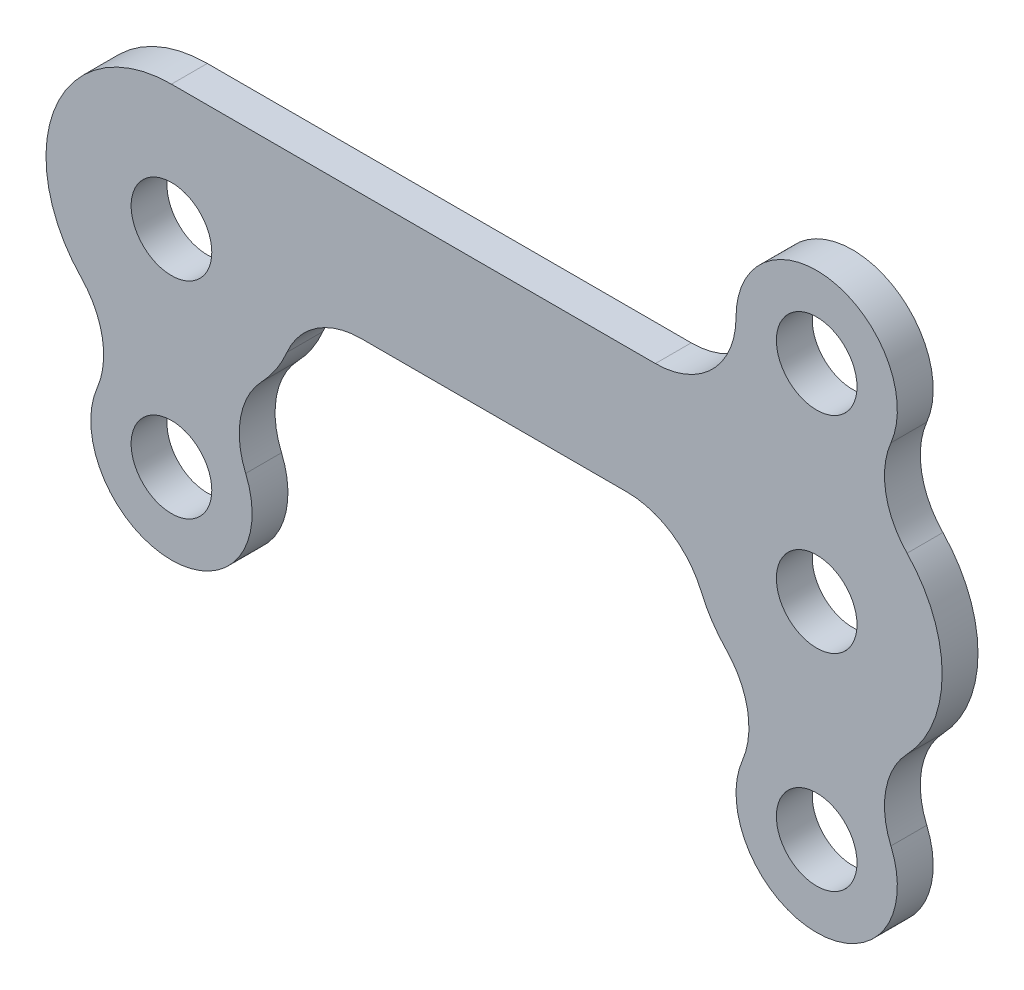
SolidWorks part; units mm, degrees
ref_plane "Front Plane" through (0, 0, 0) normal (0, 0, 1) x (1, 0, 0)
ref_plane "Top Plane" through (0, 0, 0) normal (0, 1, 0) x (1, 0, 0)
ref_plane "Right Plane" through (0, 0, 0) normal (1, 0, 0) x (0, 0, -1)
sketch "Sketch1" plane through (0, 0, 0) normal (0, 0, 1) x (1, 0, 0)
  line L0 (5.5562, 0) -> (23.0188, 0)
  line L1 (0, 5.5562) -> (28.575, 5.5562)
  line L5 (0, 5.5562) -> (28.575, 5.5562) construction
  circle A0 centre (0, 0) radius 5.5562 construction
  circle A1 centre (28.575, 0) radius 5.5562 construction
  arc A2 (0, 5.5562) -> (0, -5.5562) centre (0, 0) ccw
  arc A3 (28.575, -5.5562) -> (28.575, 5.5562) centre (28.575, 0) ccw
  circle A4 centre (0, 0) radius 1.7859
  circle A5 centre (28.575, 0) radius 1.7859
  arc A6 (0, -5.5562) -> (5.5562, 0) centre (0, 0) ccw
  arc A7 (23.0188, 0) -> (28.575, -5.5562) centre (28.575, 0) ccw
  circle A10 centre (0, -9.1281) radius 3.5719
  circle A12 centre (28.575, -9.1281) radius 1.7859
  circle A15 centre (0, -9.1281) radius 1.7859
  circle A17 centre (28.575, -9.1281) radius 3.5719
  circle A27 centre (-6.5741, -6.3327) radius 3.5719
  circle A28 centre (6.5741, -6.3327) radius 3.5719
  circle A29 centre (22.0009, -6.3327) radius 3.5719
  circle A30 centre (35.1491, -6.3327) radius 3.5719
  circle A31 centre (28.575, 9.1281) radius 1.7859
  circle A32 centre (28.575, 9.1281) radius 3.5719
  circle A33 centre (21.4313, 9.1281) radius 3.5719
  circle A34 centre (35.1491, 6.3327) radius 3.5719
  point P31 (0, 0)
  point P36 (18.3738, 10.1294)
  dimension "D1" = 28.575
  dimension "D2" = 11.1125
  dimension "D3" = 3.5719
  dimension "D6" = 7.1437
  dimension "D7" = 3.5719
extrude "Boss-Extrude1" add sketch "Sketch1" along normal blind 1.5875
fillet "Fillet1" radius 3.5719 2 edges at (23.0188, 0, 0.7937) (5.5562, 0, 0.7937)
